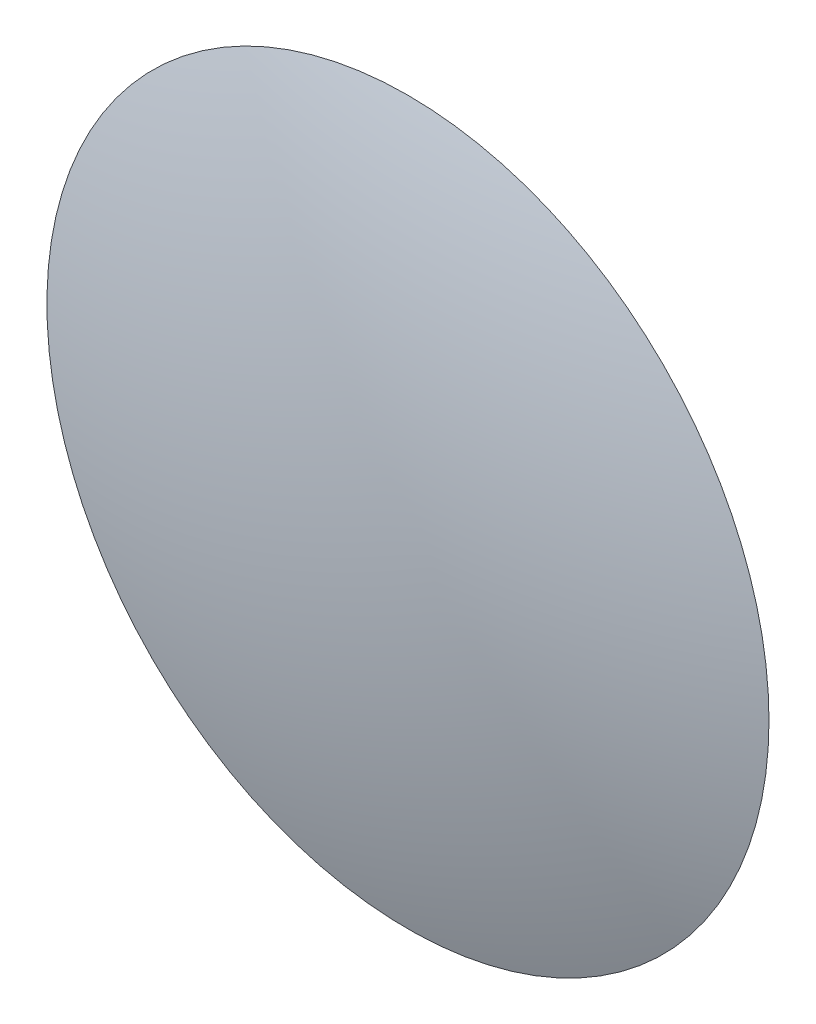
SolidWorks part; units mm, degrees
ref_plane "Front Plane" through (0, 0, 0) normal (0, 0, 1) x (1, 0, 0)
ref_plane "Top Plane" through (0, 0, 0) normal (0, 1, 0) x (1, 0, 0)
ref_plane "Right Plane" through (0, 0, 0) normal (1, 0, 0) x (0, 0, -1)
sketch "Sketch1" plane through (0, 0, 0) normal (1, 0, 0) x (0, 0, -1)
  line L0 (-34.5533, 0) -> (24.5152, 0) construction
  line L1 (0, 0) -> (0, 22.5)
  line L2 (0, 0) -> (3.5272, 0)
  arc A0 (0, 22.5) -> (3.5272, 0) centre (-70, 0) cw
  dimension "D1" = 22.5
  dimension "D2" = 70
revolve "Revolve1" add sketch "Sketch1" angle 360 about L0
mirror "Mirror1" about plane through (0, 0, 0) normal (0, 0, 1) of "Revolve1"
scale "Scale1" scale about centroid uniform scaling yes scale factor 0.75
